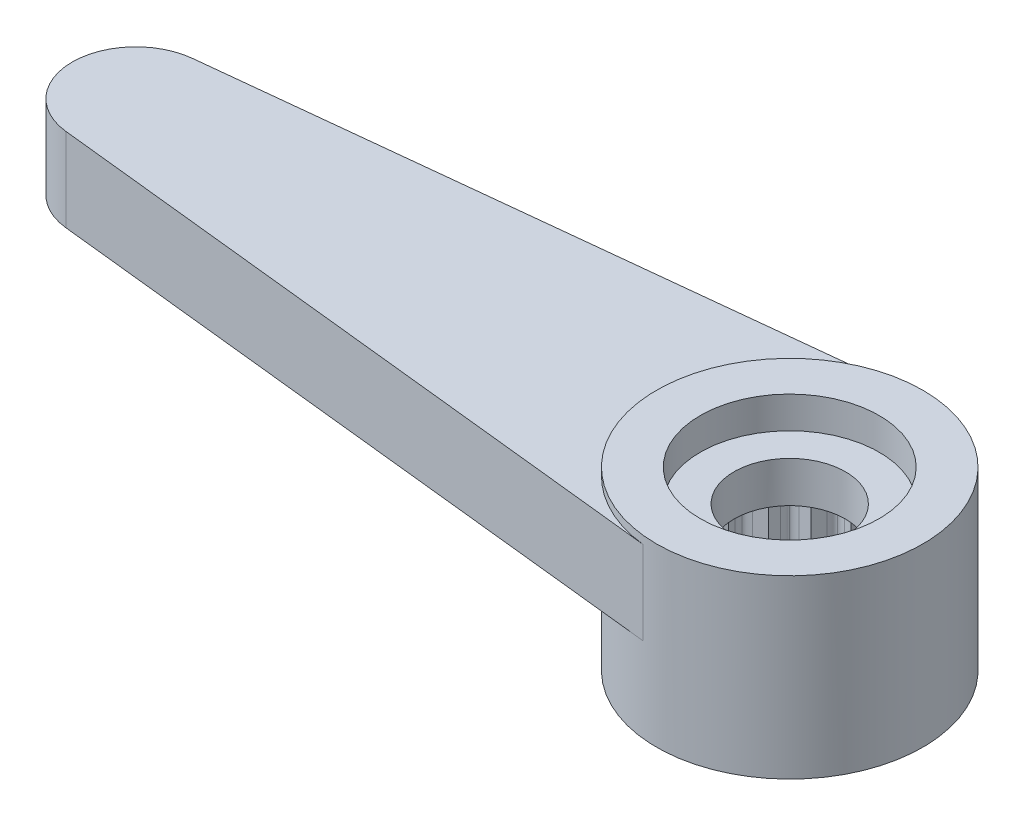
SolidWorks part; units mm, degrees
ref_plane "Front Plane" through (0, 0, 0) normal (0, 0, 1) x (1, 0, 0)
ref_plane "Top Plane" through (0, 0, 0) normal (0, 1, 0) x (1, 0, 0)
ref_plane "Right Plane" through (0, 0, 0) normal (1, 0, 0) x (0, 0, -1)
sketch "Sketch1" plane through (0, 0, 0) normal (0, 1, 0) x (1, 0, 0)
  line L0 (8.5192, 3.1352) -> (-7.7447, 1.3951)
  line L1 (-7.5744, -0.1958) -> (8.8756, -0.1958) construction
  line L2 (8.5192, -3.5268) -> (-7.7447, -1.7867)
  circle A0 centre (8.8756, -0.1958) radius 3.35 construction
  circle A1 centre (-7.5744, -0.1958) radius 1.6 construction
  arc A2 (-7.7447, 1.3951) -> (-7.7447, -1.7867) centre (-7.5744, -0.1958) ccw
  arc A3 (8.5192, 3.1352) -> (8.5192, -3.5268) centre (8.8756, -0.1958) cw
  point P8 (-9.1744, -0.1958)
  point P9 (12.2256, -0.1958)
  dimension "D1" = 6.7
  dimension "D2" = 3.2
  dimension "D3" = 21.4
extrude "Boss-Extrude1" add sketch "Sketch1" along normal blind 2.1 contours L2 A2 L0 A3
sketch "Sketch2" plane through (0, 2.1, 0) normal (0, 1, 0) x (1, 0, 0)
  circle A0 centre (8.8756, -0.1958) radius 3.35
extrude "Boss-Extrude2" add sketch "Sketch2" along normal blind 0.2
sketch "Sketch3" plane through (0, 2.3, 0) normal (0, 1, 0) x (1, 0, 0)
  circle A0 centre (8.8756, -0.1958) radius 2.25
  dimension "D1" = 4.5
extrude "Cut-Extrude1" cut sketch "Sketch3" against normal blind 0.8
sketch "Sketch4" plane through (0, 0, 0) normal (0, -1, 0) x (1, 0, 0)
  circle A0 centre (8.8756, 0.1958) radius 3.35 construction
  circle A1 centre (8.8756, 0.1958) radius 3.35
extrude "Boss-Extrude3" add sketch "Sketch4" along normal blind 2.13
sketch "Sketch5" plane through (0, -2.13, 0) normal (0, -1, 0) x (1, 0, 0)
  line L0 (8.8756, 0.1958) -> (8.8756, 2.5958) construction
  line L1 (8.8756, 0.1958) -> (8.1339, 2.4783) construction
  line L2 (8.8756, 0.1958) -> (8.5001, 2.5662) construction
  line L3 (8.1339, 2.4783) -> (8.3018, 2.7758)
  line L4 (8.3018, 2.7758) -> (8.3788, 2.9121) construction
  line L5 (8.3788, 2.9121) -> (8.4457, 2.91) construction
  line L6 (8.624, 2.8268) -> (8.5086, 2.9327) construction
  line L7 (8.5086, 2.9327) -> (8.4457, 2.91) construction
  line L8 (8.8756, 2.5958) -> (8.624, 2.8268)
  line L9 (8.8756, 2.5958) -> (9.1272, 2.8268)
  line L10 (9.6172, 2.4783) -> (9.4493, 2.7758)
  line L11 (9.1272, 2.8268) -> (9.2425, 2.9327) construction
  line L12 (9.2425, 2.9327) -> (9.3055, 2.91) construction
  line L13 (9.4493, 2.7758) -> (9.3724, 2.9121) construction
  line L14 (9.3724, 2.9121) -> (9.3055, 2.91) construction
  line L15 (9.6172, 2.4783) -> (9.9279, 2.6203)
  line L16 (10.2862, 2.1374) -> (10.2185, 2.4722)
  line L17 (9.9279, 2.6203) -> (10.0703, 2.6854) construction
  line L18 (10.0703, 2.6854) -> (10.1232, 2.6443) construction
  line L19 (10.2185, 2.4722) -> (10.1874, 2.6257) construction
  line L20 (10.1874, 2.6257) -> (10.1232, 2.6443) construction
  line L21 (10.2862, 2.1374) -> (10.6256, 2.1764)
  line L22 (10.8172, 1.6065) -> (10.8562, 1.9458)
  line L23 (10.6256, 2.1764) -> (10.7811, 2.1943) construction
  line L24 (10.7811, 2.1943) -> (10.8187, 2.139) construction
  line L25 (10.8562, 1.9458) -> (10.8741, 2.1013) construction
  line L26 (10.8741, 2.1013) -> (10.8187, 2.139) construction
  line L27 (10.8172, 1.6065) -> (11.152, 1.5387)
  line L28 (11.1581, 0.9374) -> (11.3001, 1.2481)
  line L29 (11.152, 1.5387) -> (11.3054, 1.5077) construction
  line L30 (11.3054, 1.5077) -> (11.3241, 1.4434) construction
  line L31 (11.3001, 1.2481) -> (11.3651, 1.3905) construction
  line L32 (11.3651, 1.3905) -> (11.3241, 1.4434) construction
  line L33 (11.1581, 0.9374) -> (11.4556, 0.7695)
  line L34 (11.2756, 0.1958) -> (11.5066, 0.4474)
  line L35 (11.4556, 0.7695) -> (11.5919, 0.6926) construction
  line L36 (11.5919, 0.6926) -> (11.5898, 0.6257) construction
  line L37 (11.5066, 0.4474) -> (11.6125, 0.5627) construction
  line L38 (11.6125, 0.5627) -> (11.5898, 0.6257) construction
  line L39 (11.2756, 0.1958) -> (11.5066, -0.0558)
  line L40 (11.1581, -0.5459) -> (11.4556, -0.378)
  line L41 (11.5066, -0.0558) -> (11.6125, -0.1711) construction
  line L42 (11.6125, -0.1711) -> (11.5898, -0.2341) construction
  line L43 (11.4556, -0.378) -> (11.5919, -0.301) construction
  line L44 (11.5919, -0.301) -> (11.5898, -0.2341) construction
  line L45 (11.1581, -0.5459) -> (11.3001, -0.8566)
  line L46 (10.8172, -1.2149) -> (11.152, -1.1471)
  line L47 (11.3001, -0.8566) -> (11.3651, -0.9989) construction
  line L48 (11.3651, -0.9989) -> (11.3241, -1.0518) construction
  line L49 (11.152, -1.1471) -> (11.3054, -1.1161) construction
  line L50 (11.3054, -1.1161) -> (11.3241, -1.0518) construction
  line L51 (10.8172, -1.2149) -> (10.8562, -1.5543)
  line L52 (10.2862, -1.7459) -> (10.6256, -1.7849)
  line L53 (10.8562, -1.5543) -> (10.8741, -1.7098) construction
  line L54 (10.8741, -1.7098) -> (10.8187, -1.7474) construction
  line L55 (10.6256, -1.7849) -> (10.7811, -1.8028) construction
  line L56 (10.7811, -1.8028) -> (10.8187, -1.7474) construction
  line L57 (10.2862, -1.7459) -> (10.2185, -2.0807)
  line L58 (9.6172, -2.0868) -> (9.9279, -2.2287)
  line L59 (10.2185, -2.0807) -> (10.1874, -2.2341) construction
  line L60 (10.1874, -2.2341) -> (10.1232, -2.2528) construction
  line L61 (9.9279, -2.2287) -> (10.0703, -2.2938) construction
  line L62 (10.0703, -2.2938) -> (10.1232, -2.2528) construction
  line L63 (9.6172, -2.0868) -> (9.4493, -2.3842)
  line L64 (8.8756, -2.2042) -> (9.1272, -2.4353)
  line L65 (9.4493, -2.3842) -> (9.3724, -2.5206) construction
  line L66 (9.3724, -2.5206) -> (9.3055, -2.5184) construction
  line L67 (9.1272, -2.4353) -> (9.2425, -2.5411) construction
  line L68 (9.2425, -2.5411) -> (9.3055, -2.5184) construction
  line L69 (8.8756, -2.2042) -> (8.624, -2.4353)
  line L70 (8.1339, -2.0868) -> (8.3018, -2.3842)
  line L71 (8.624, -2.4353) -> (8.5086, -2.5411) construction
  line L72 (8.5086, -2.5411) -> (8.4457, -2.5184) construction
  line L73 (8.3018, -2.3842) -> (8.3788, -2.5206) construction
  line L74 (8.3788, -2.5206) -> (8.4457, -2.5184) construction
  line L75 (8.1339, -2.0868) -> (7.8232, -2.2287)
  line L76 (7.4649, -1.7459) -> (7.5326, -2.0807)
  line L77 (7.8232, -2.2287) -> (7.6808, -2.2938) construction
  line L78 (7.6808, -2.2938) -> (7.628, -2.2528) construction
  line L79 (7.5326, -2.0807) -> (7.5637, -2.2341) construction
  line L80 (7.5637, -2.2341) -> (7.628, -2.2528) construction
  line L81 (7.4649, -1.7459) -> (7.1255, -1.7849)
  line L82 (6.9339, -1.2149) -> (6.8949, -1.5543)
  line L83 (7.1255, -1.7849) -> (6.97, -1.8028) construction
  line L84 (6.97, -1.8028) -> (6.9324, -1.7474) construction
  line L85 (6.8949, -1.5543) -> (6.877, -1.7098) construction
  line L86 (6.877, -1.7098) -> (6.9324, -1.7474) construction
  line L87 (6.9339, -1.2149) -> (6.5991, -1.1471)
  line L88 (6.593, -0.5459) -> (6.451, -0.8566)
  line L89 (6.5991, -1.1471) -> (6.4457, -1.1161) construction
  line L90 (6.4457, -1.1161) -> (6.427, -1.0518) construction
  line L91 (6.451, -0.8566) -> (6.386, -0.9989) construction
  line L92 (6.386, -0.9989) -> (6.427, -1.0518) construction
  line L93 (6.593, -0.5459) -> (6.2955, -0.378)
  line L94 (6.4756, 0.1958) -> (6.2445, -0.0558)
  line L95 (6.2955, -0.378) -> (6.1592, -0.301) construction
  line L96 (6.1592, -0.301) -> (6.1613, -0.2341) construction
  line L97 (6.2445, -0.0558) -> (6.1386, -0.1711) construction
  line L98 (6.1386, -0.1711) -> (6.1613, -0.2341) construction
  line L99 (6.4756, 0.1958) -> (6.2445, 0.4474)
  line L100 (6.593, 0.9374) -> (6.2955, 0.7695)
  line L101 (6.2445, 0.4474) -> (6.1386, 0.5627) construction
  line L102 (6.1386, 0.5627) -> (6.1613, 0.6257) construction
  line L103 (6.2955, 0.7695) -> (6.1592, 0.6926) construction
  line L104 (6.1592, 0.6926) -> (6.1613, 0.6257) construction
  line L105 (6.593, 0.9374) -> (6.451, 1.2481)
  line L106 (6.9339, 1.6065) -> (6.5991, 1.5387)
  line L107 (6.451, 1.2481) -> (6.386, 1.3905) construction
  line L108 (6.386, 1.3905) -> (6.427, 1.4434) construction
  line L109 (6.5991, 1.5387) -> (6.4457, 1.5077) construction
  line L110 (6.4457, 1.5077) -> (6.427, 1.4434) construction
  line L111 (6.9339, 1.6065) -> (6.8949, 1.9458)
  line L112 (7.4649, 2.1374) -> (7.1255, 2.1764)
  line L113 (6.8949, 1.9458) -> (6.877, 2.1013) construction
  line L114 (6.877, 2.1013) -> (6.9324, 2.139) construction
  line L115 (7.1255, 2.1764) -> (6.97, 2.1943) construction
  line L116 (6.97, 2.1943) -> (6.9324, 2.139) construction
  line L117 (7.4649, 2.1374) -> (7.5326, 2.4722)
  line L118 (8.1339, 2.4783) -> (7.8232, 2.6203)
  line L119 (7.5326, 2.4722) -> (7.5637, 2.6257) construction
  line L120 (7.5637, 2.6257) -> (7.628, 2.6443) construction
  line L121 (7.8232, 2.6203) -> (7.6808, 2.6854) construction
  line L122 (7.6808, 2.6854) -> (7.628, 2.6443) construction
  circle A0 centre (8.8756, 0.1958) radius 2.4 construction
  arc A1 (8.8756, 2.5958) -> (8.1339, 2.4783) centre (8.8756, 0.1958) ccw construction
  spline S0 degree 2 poles (8.3018, 2.7758) (8.3788, 2.9121) (8.4457, 2.91) knots 0 0 0 1 1 1
  spline S1 degree 2 poles (8.624, 2.8268) (8.5086, 2.9327) (8.4457, 2.91) knots 0 0 0 1 1 1
  spline S2 degree 2 poles (9.4493, 2.7758) (9.3724, 2.9121) (9.3055, 2.91) knots 0 0 0 1 1 1
  spline S3 degree 2 poles (9.1272, 2.8268) (9.2425, 2.9327) (9.3055, 2.91) knots 0 0 0 1 1 1
  spline S4 degree 2 poles (10.2185, 2.4722) (10.1874, 2.6257) (10.1232, 2.6443) knots 0 0 0 1 1 1
  spline S5 degree 2 poles (9.9279, 2.6203) (10.0703, 2.6854) (10.1232, 2.6443) knots 0 0 0 1 1 1
  spline S6 degree 2 poles (10.8562, 1.9458) (10.8741, 2.1013) (10.8187, 2.139) knots 0 0 0 1 1 1
  spline S7 degree 2 poles (10.6256, 2.1764) (10.7811, 2.1943) (10.8187, 2.139) knots 0 0 0 1 1 1
  spline S8 degree 2 poles (11.3001, 1.2481) (11.3651, 1.3905) (11.3241, 1.4434) knots 0 0 0 1 1 1
  spline S9 degree 2 poles (11.152, 1.5387) (11.3054, 1.5077) (11.3241, 1.4434) knots 0 0 0 1 1 1
  spline S10 degree 2 poles (11.5066, 0.4474) (11.6125, 0.5627) (11.5898, 0.6257) knots 0 0 0 1 1 1
  spline S11 degree 2 poles (11.4556, 0.7695) (11.5919, 0.6926) (11.5898, 0.6257) knots 0 0 0 1 1 1
  spline S12 degree 2 poles (11.4556, -0.378) (11.5919, -0.301) (11.5898, -0.2341) knots 0 0 0 1 1 1
  spline S13 degree 2 poles (11.5066, -0.0558) (11.6125, -0.1711) (11.5898, -0.2341) knots 0 0 0 1 1 1
  spline S14 degree 2 poles (11.152, -1.1471) (11.3054, -1.1161) (11.3241, -1.0518) knots 0 0 0 1 1 1
  spline S15 degree 2 poles (11.3001, -0.8566) (11.3651, -0.9989) (11.3241, -1.0518) knots 0 0 0 1 1 1
  spline S16 degree 2 poles (10.6256, -1.7849) (10.7811, -1.8028) (10.8187, -1.7474) knots 0 0 0 1 1 1
  spline S17 degree 2 poles (10.8562, -1.5543) (10.8741, -1.7098) (10.8187, -1.7474) knots 0 0 0 1 1 1
  spline S18 degree 2 poles (9.9279, -2.2287) (10.0703, -2.2938) (10.1232, -2.2528) knots 0 0 0 1 1 1
  spline S19 degree 2 poles (10.2185, -2.0807) (10.1874, -2.2341) (10.1232, -2.2528) knots 0 0 0 1 1 1
  spline S20 degree 2 poles (9.1272, -2.4353) (9.2425, -2.5411) (9.3055, -2.5184) knots 0 0 0 1 1 1
  spline S21 degree 2 poles (9.4493, -2.3842) (9.3724, -2.5206) (9.3055, -2.5184) knots 0 0 0 1 1 1
  spline S22 degree 2 poles (8.3018, -2.3842) (8.3788, -2.5206) (8.4457, -2.5184) knots 0 0 0 1 1 1
  spline S23 degree 2 poles (8.624, -2.4353) (8.5086, -2.5411) (8.4457, -2.5184) knots 0 0 0 1 1 1
  spline S24 degree 2 poles (7.5326, -2.0807) (7.5637, -2.2341) (7.628, -2.2528) knots 0 0 0 1 1 1
  spline S25 degree 2 poles (7.8232, -2.2287) (7.6808, -2.2938) (7.628, -2.2528) knots 0 0 0 1 1 1
  spline S26 degree 2 poles (6.8949, -1.5543) (6.877, -1.7098) (6.9324, -1.7474) knots 0 0 0 1 1 1
  spline S27 degree 2 poles (7.1255, -1.7849) (6.97, -1.8028) (6.9324, -1.7474) knots 0 0 0 1 1 1
  spline S28 degree 2 poles (6.451, -0.8566) (6.386, -0.9989) (6.427, -1.0518) knots 0 0 0 1 1 1
  spline S29 degree 2 poles (6.5991, -1.1471) (6.4457, -1.1161) (6.427, -1.0518) knots 0 0 0 1 1 1
  spline S30 degree 2 poles (6.2445, -0.0558) (6.1386, -0.1711) (6.1613, -0.2341) knots 0 0 0 1 1 1
  spline S31 degree 2 poles (6.2955, -0.378) (6.1592, -0.301) (6.1613, -0.2341) knots 0 0 0 1 1 1
  spline S32 degree 2 poles (6.2955, 0.7695) (6.1592, 0.6926) (6.1613, 0.6257) knots 0 0 0 1 1 1
  spline S33 degree 2 poles (6.2445, 0.4474) (6.1386, 0.5627) (6.1613, 0.6257) knots 0 0 0 1 1 1
  spline S34 degree 2 poles (6.5991, 1.5387) (6.4457, 1.5077) (6.427, 1.4434) knots 0 0 0 1 1 1
  spline S35 degree 2 poles (6.451, 1.2481) (6.386, 1.3905) (6.427, 1.4434) knots 0 0 0 1 1 1
  spline S36 degree 2 poles (7.1255, 2.1764) (6.97, 2.1943) (6.9324, 2.139) knots 0 0 0 1 1 1
  spline S37 degree 2 poles (6.8949, 1.9458) (6.877, 2.1013) (6.9324, 2.139) knots 0 0 0 1 1 1
  spline S38 degree 2 poles (7.8232, 2.6203) (7.6808, 2.6854) (7.628, 2.6443) knots 0 0 0 1 1 1
  spline S39 degree 2 poles (7.5326, 2.4722) (7.5637, 2.6257) (7.628, 2.6443) knots 0 0 0 1 1 1
  point P146 (8.8756, 0.1958)
  dimension "D1" = 4.8
  dimension "D2" = 18
  dimension "D3" = 20
extrude "Cut-Extrude2" cut sketch "Sketch5" against normal blind 2.6
sketch "Sketch6" plane through (0, 1.5, 0) normal (0, 1, 0) x (1, 0, 0)
  circle A0 centre (8.8756, -0.1958) radius 1.4
  dimension "D1" = 2.8
extrude "Cut-Extrude3" cut sketch "Sketch6" against normal through all both and the other way through all
